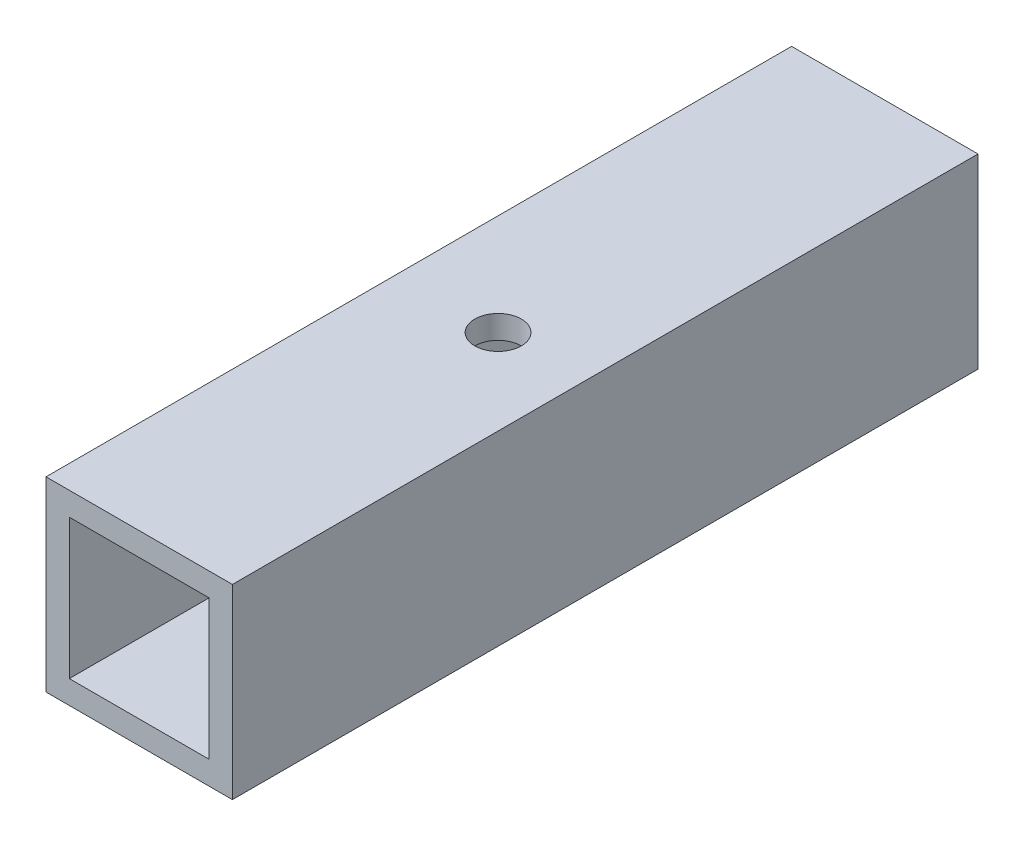
SolidWorks part; units mm, degrees
ref_plane "Front Plane" through (0, 0, 0) normal (0, 0, 1) x (1, 0, 0)
ref_plane "Top Plane" through (0, 0, 0) normal (0, 1, 0) x (1, 0, 0)
ref_plane "Right Plane" through (0, 0, 0) normal (1, 0, 0) x (0, 0, -1)
sketch "Sketch1" plane through (0, 0, 0) normal (0, 0, 1) x (1, 0, 0)
  line L0 (3.175, 22.225) -> (22.225, 22.225)
  line L1 (0, 0) -> (25.4, 0)
  line L2 (0, 0) -> (0, 25.4)
  line L3 (0, 25.4) -> (25.4, 25.4)
  line L4 (25.4, 0) -> (25.4, 25.4)
  line L5 (0, 0) -> (25.4, 25.4) construction
  line L6 (0, 25.4) -> (25.4, 0) construction
  line L7 (22.225, 3.175) -> (22.225, 22.225)
  line L8 (3.175, 3.175) -> (22.225, 3.175)
  line L9 (3.175, 3.175) -> (3.175, 22.225)
  point P4 (12.7, 12.7)
  dimension "D1" = 25.4
  dimension "D2" = 3.175
extrude "Boss-Extrude1" add sketch "Sketch1" along normal blind 101.6
sketch "Sketch2" plane through (0, 25.4, 0) normal (0, 1, 0) x (1, 0, 0)
  ellipse E0 centre (13.7664, -53.7644) end of major axis (11.2262, -51.8597) minor radius 3.1736 construction
  ellipse E1 centre (13.7664, -53.7644) end of major axis (16.3066, -55.6692) minor radius 3.1736
extrude "Cut-Extrude1" cut sketch "Sketch2" against normal blind 101.6
